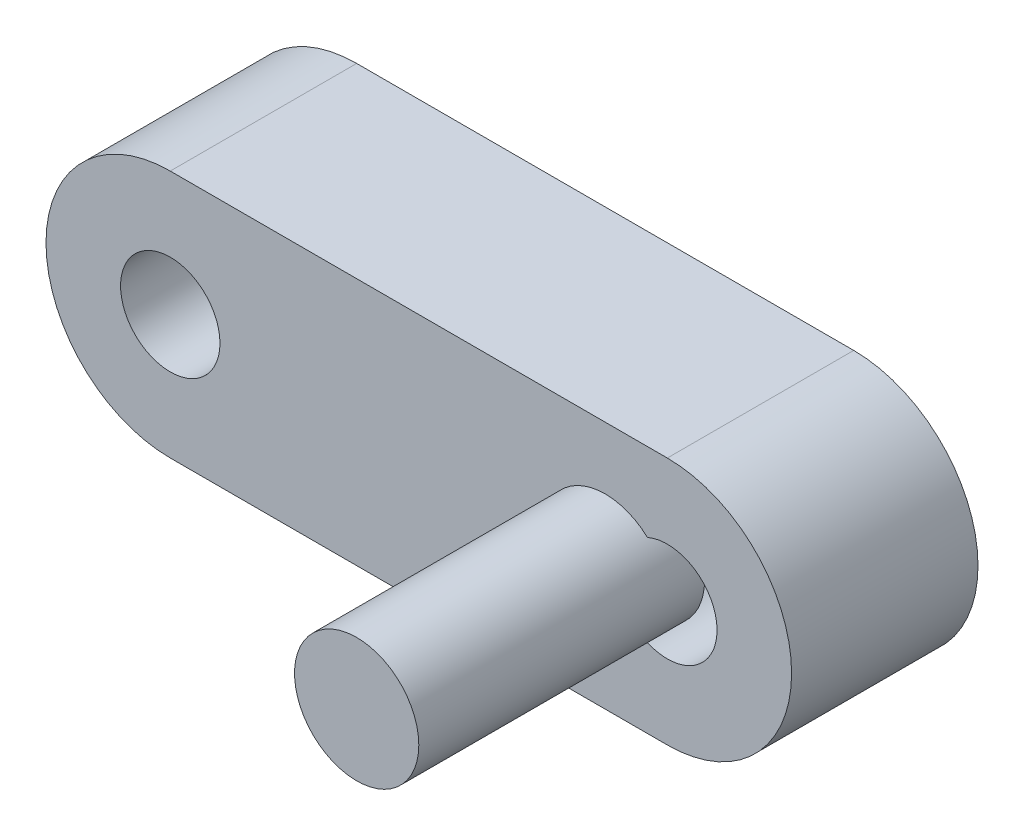
SolidWorks part; units mm, degrees
material "ABS"
ref_plane "前基準面" through (0, 0, 0) normal (0, 0, 1) x (1, 0, 0)
ref_plane "上基準面" through (0, 0, 0) normal (0, 1, 0) x (1, 0, 0)
ref_plane "右基準面" through (0, 0, 0) normal (1, 0, 0) x (0, 0, -1)
sketch "草圖1" plane through (0, 0, 0) normal (0, 0, 1) x (1, 0, 0)
  line L0 (-10, 0) -> (10, 0) construction
  line L1 (-10, 5) -> (10, 5)
  line L2 (-10, -5) -> (10, -5)
  arc A0 (-10, 5) -> (-10, -5) centre (-10, 0) ccw
  arc A1 (10, -5) -> (10, 5) centre (10, 0) ccw
  circle A2 centre (-10, 0) radius 2
  circle A3 centre (10, 0) radius 2
  point P3 (0, 0)
  dimension "D1" = 5
  dimension "D3" = 4
  dimension "D4" = 4
  dimension "D2" = 20
extrude "填料-伸長1" add sketch "草圖1" along normal blind 7.5
sketch "草圖2" plane through (0, 0, 7.5) normal (0, 0, 1) x (1, 0, 0)
  circle A0 centre (7.5, 0) radius 2.5
  dimension "D1" = 5
extrude "填料-伸長2" add sketch "草圖2" along normal blind 10 and the other way blind 1.5
sketch "草圖5" plane through (0, 0, 0) normal (0, 0, -1) x (-1, 0, 0)
  line L1 (5.8822, -2.7993) -> (9.1154, -2.8007)
  line L2 (9.1154, -2.8007) -> (10.7332, -0.0014)
  line L3 (10.7332, -0.0014) -> (9.1178, 2.7993)
  line L4 (9.1178, 2.7993) -> (5.8846, 2.8007)
  line L5 (5.8846, 2.8007) -> (4.2668, 0.0014)
  line L6 (4.2668, 0.0014) -> (5.8822, -2.7993)
  circle A0 centre (7.5, 0) radius 2.8 construction
  circle A1 centre (-10, 0) radius 3.1
  dimension "D2" = 6.2
  dimension "D1" = 5.6
extrude "除料-伸長1" cut sketch "草圖5" against normal blind 4
